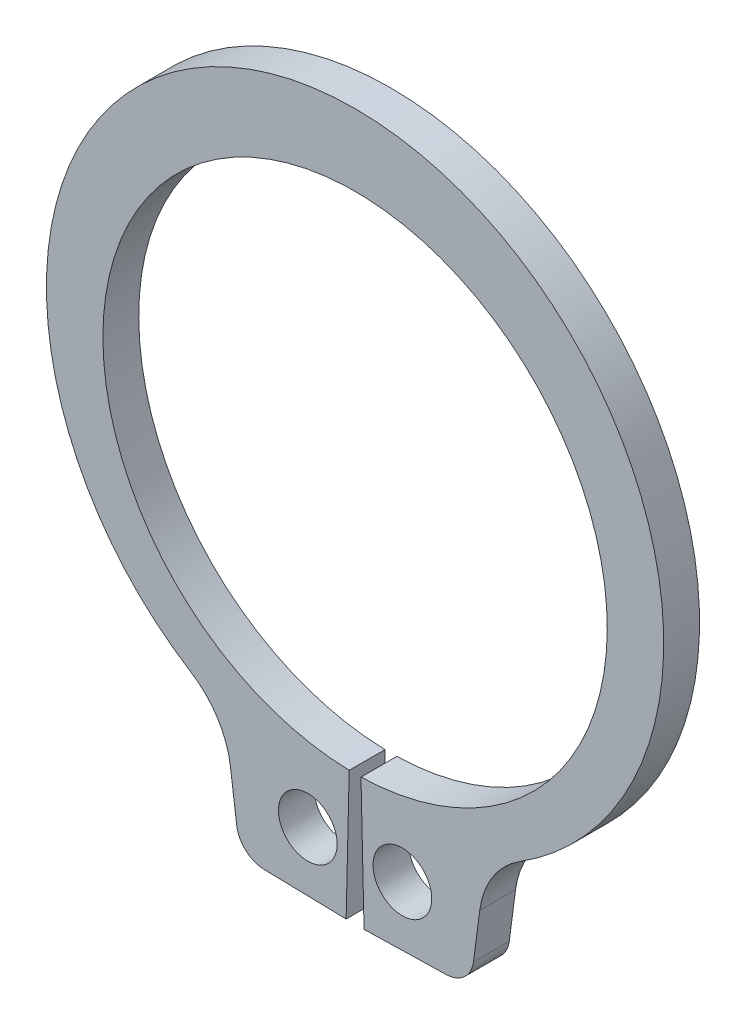
SolidWorks part; units mm, degrees
material "AISI 1020 Steel, Cold Rolled"
ref_plane "Plane1" through (0, 0, 0) normal (0, 0, 1) x (1, 0, 0)
ref_plane "Plane2" through (0, 0, 0) normal (0, 1, 0) x (1, 0, 0)
ref_plane "Plane3" through (0, 0, 0) normal (1, 0, 0) x (0, 0, -1)
sketch "BodySke" plane through (0, 0, 0) normal (0, 0, 1) x (1, 0, 0)
  line L0 (-1.5431, 0) -> (1.5431, 0) construction
  line L1 (0, 0) -> (0, 5.7404) construction
  line L2 (0.1046, -4.4692) -> (0.1588, -6.7799)
  line L3 (-0.1046, -4.4692) -> (-0.1588, -6.7799)
  line L4 (0, 0) -> (3.7331, -5.6618) construction
  line L5 (0, 0) -> (-3.7331, -5.6618) construction
  line L6 (0.1588, -6.7799) -> (1.6141, -6.7459)
  line L7 (2.21, -5.4613) -> (2.0981, -6.3113)
  line L8 (-2.21, -5.4613) -> (-2.0981, -6.3113)
  line L9 (-0.1588, -6.7799) -> (-1.6141, -6.7459)
  circle A0 centre (0, 0) radius 4.4704 construction
  arc A1 (0.1046, -4.4692) -> (-0.1046, -4.4692) centre (0, 0) ccw
  arc A2 (2.8872, -4.3789) -> (-2.8872, -4.3789) centre (0, 0.2688) ccw construction
  arc A3 (0.1588, -6.7799) -> (1.6983, -6.5657) centre (0, 0) ccw construction
  arc A4 (2.9148, -4.3617) -> (2.21, -5.4613) centre (3.7331, -5.6618) ccw
  arc A5 (-2.21, -5.4613) -> (-2.9148, -4.3617) centre (-3.7331, -5.6618) ccw
  arc A6 (-1.6983, -6.5657) -> (-0.1588, -6.7799) centre (0, 0) ccw construction
  arc A7 (2.9148, -4.3617) -> (-2.9148, -4.3617) centre (0, 0.2688) ccw
  arc A8 (-2.228, -5.3248) -> (2.228, -5.3248) centre (0, 0) ccw construction
  circle A9 centre (0.8382, -5.711) radius 0.5207
  circle A10 centre (-0.8382, -5.711) radius 0.5207
  arc A11 (2.0981, -6.3113) -> (1.6141, -6.7459) centre (1.6024, -6.246) cw
  arc A12 (-2.0981, -6.3113) -> (-1.6141, -6.7459) centre (-1.6024, -6.246) ccw
  point P28 (2.0792, -6.4552)
  point P31 (-2.0792, -6.4552)
  dimension "GrooveDia" = 8.9408
  dimension "LugRad" = 6.7818
  dimension "HoleOffsetRad" = 5.7721
  dimension "HoleDia" = 1.0414
  dimension "D3" = 0.5
  dimension "LargeRad" = 5.7404
  dimension "SmallRad" = 5.2451
  dimension "SmallAngle" = 66.798
  dimension "D2" = 15
  dimension "HoleSpacing" = 1.6764
  dimension "Gap" = 0.3175
extrude "Body" add sketch "BodySke" against normal blind 0.635
equation "\"Gap@BodySke\" =  \"Thickness@Body\" / 2"
equation "\"SmallAngle@BodySke\" = atn(\"HoleSpacing@BodySke\" / 2 / sqr(\"HoleOffsetRad@BodySke\"  * \"HoleOffsetRad@BodySke\" - (\"HoleSpacing@BodySke\" / 2) * (\"HoleSpacing@BodySke\" / 2) ))  * 8 * ( 180 / 3.141593)"
